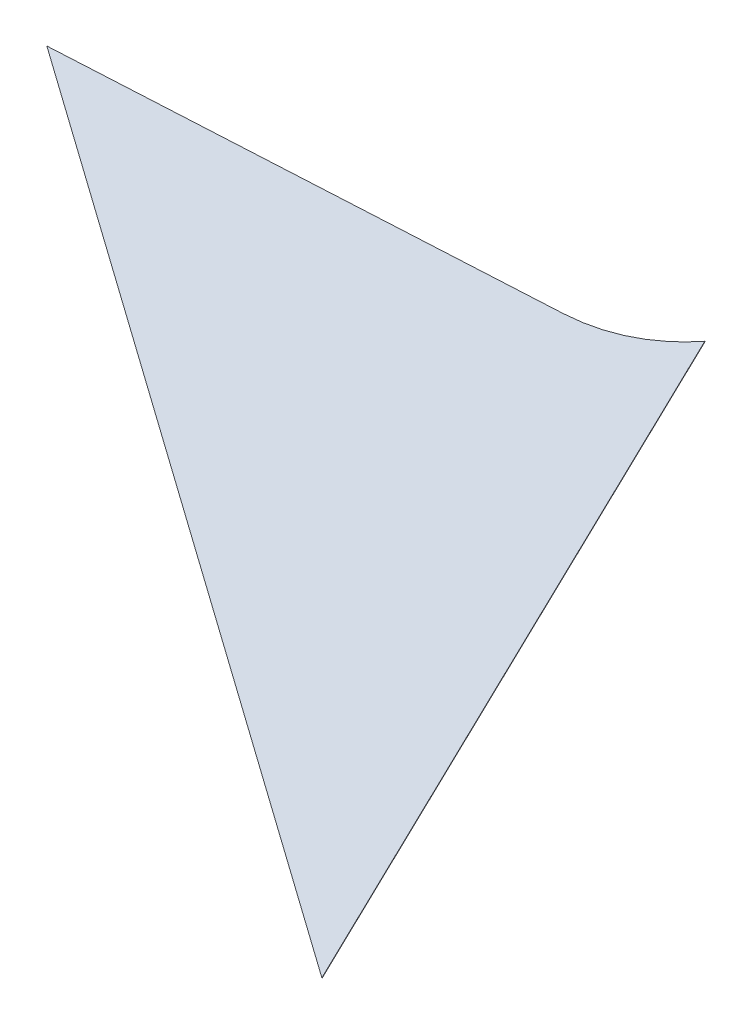
SolidWorks part; units mm, degrees
ref_plane "Front Plane" through (0, 0, 0) normal (0, 0, 1) x (1, 0, 0)
ref_plane "Top Plane" through (0, 0, 0) normal (0, 1, 0) x (1, 0, 0)
ref_plane "Right Plane" through (0, 0, 0) normal (1, 0, 0) x (0, 0, -1)
sketch "Tube Reference" plane through (-109.6499, -282.837, -713.5959) normal (0.0448, -0.758, -0.6507) x (0.9985, 0.0553, 0.0043)
  line L0 (-198.1385, 135.9025) -> (198.1385, 135.9025) construction
  line L1 (235, 127.1506) -> (235, 636.1411) construction
  line L2 (-198.1385, 135.9025) -> (198.1385, 135.9025)
  line L3 (235, 127.1506) -> (235, 636.1411)
  ellipse E0 centre (198.1385, 53.9057) end of major axis (280.1385, 53.9057) minor radius 81.9968 (263.9927, 102.7631) -> (198.1385, 135.9025) ccw construction
  ellipse E1 centre (198.1385, 53.9057) end of major axis (280.1385, 53.9057) minor radius 81.9968 (263.9927, 102.7631) -> (198.1385, 135.9025) ccw
sketch "Sketch2" plane through (-109.6499, -282.837, -713.5959) normal (0.0448, -0.758, -0.6507) x (0.9985, 0.0553, 0.0043)
  line L0 (-198.1385, 135.9025) -> (198.1385, 135.9025) construction
  line L1 (235, 127.1506) -> (235, 636.1411) construction
  line L2 (40.5227, 135.9025) -> (198.1385, 135.9025)
  line L3 (235, 127.1506) -> (235, 287.1081)
  line L4 (235, 127.1506) -> (235, 636.1411) construction
  line L5 (235, 287.1081) -> (40.5227, 135.9025)
  ellipse E0 centre (198.1385, 53.9057) end of major axis (280.1385, 53.9057) minor radius 81.9968 (263.9927, 102.7631) -> (198.1385, 135.9025) ccw construction
  ellipse E1 centre (198.1385, 53.9057) end of major axis (280.1385, 53.9057) minor radius 81.9968 (235, 127.1506) -> (198.1385, 135.9025) ccw
  point P2 (0, 0)
extrude "Boss-Extrude1" add sketch "Sketch2" along normal mid plane 0.1524
sketch "Sketch3" plane through (-109.6499, -282.837, -713.5959) normal (0.0448, -0.758, -0.6507) x (0.9985, 0.0553, 0.0043)
  point P0 (206.4576, 154.3059)
